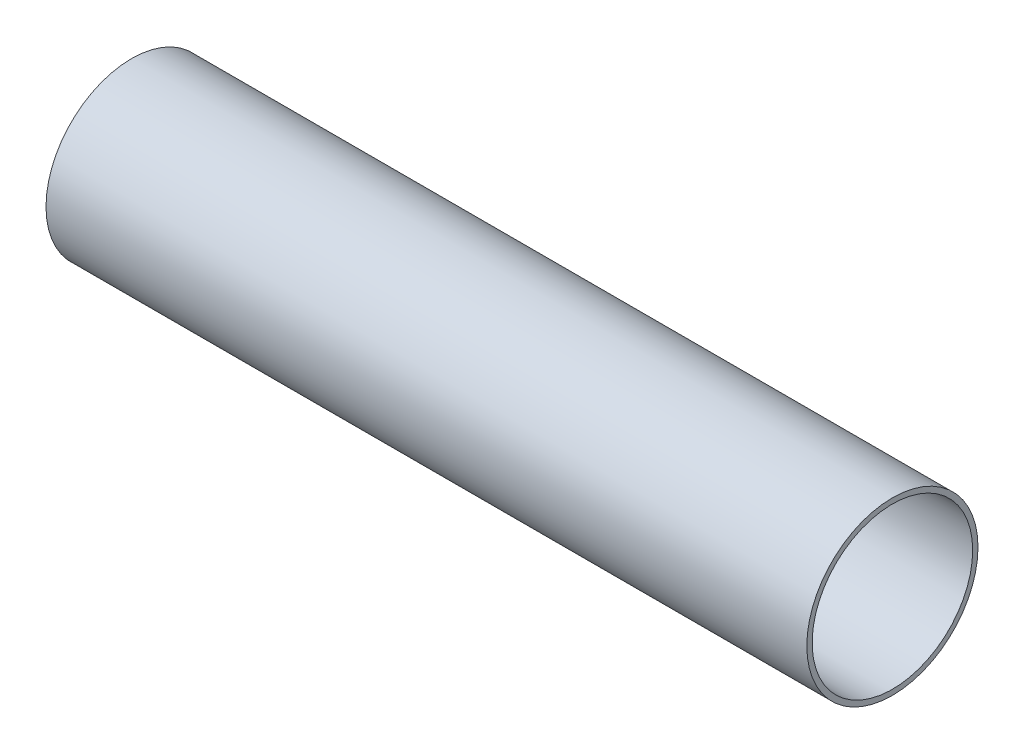
SolidWorks part; units mm, degrees
ref_plane "Front Plane" through (0, 0, 0) normal (0, 0, 1) x (1, 0, 0)
ref_plane "Top Plane" through (0, 0, 0) normal (0, 1, 0) x (1, 0, 0)
ref_plane "Right Plane" through (0, 0, 0) normal (1, 0, 0) x (0, 0, -1)
sketch "Sketch1" plane through (0, 0, 0) normal (1, 0, 0) x (0, 0, -1)
  circle A0 centre (0, 0) radius 14.2875
  circle A1 centre (0, 0) radius 13.3985
extrude "Boss-Extrude1" add sketch "Sketch1" along normal mid plane 127
